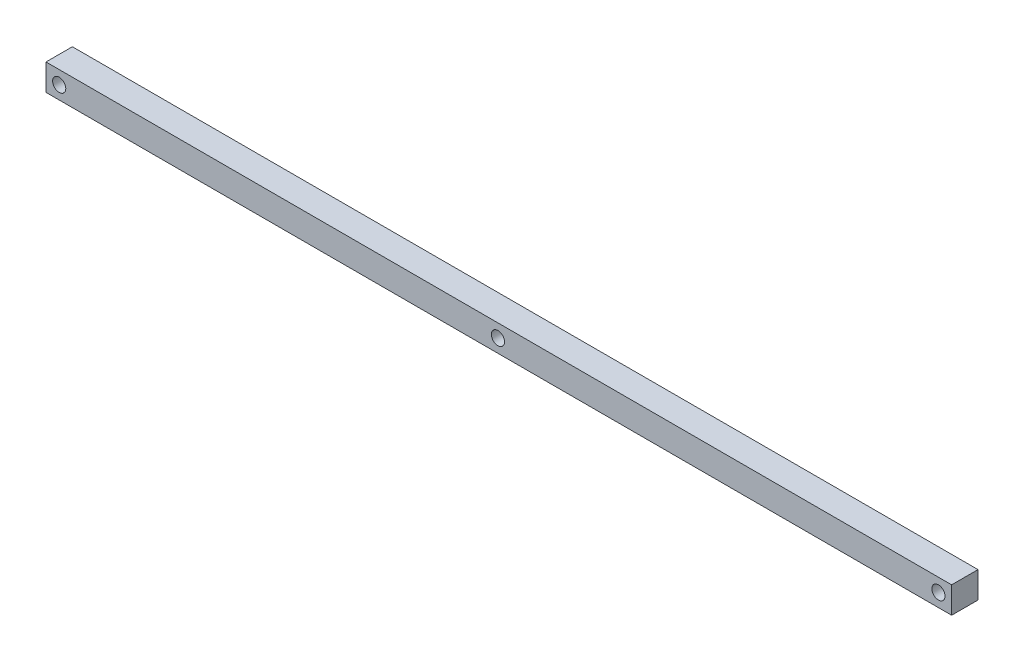
SolidWorks part; units mm, degrees
ref_plane "Front Plane" through (0, 0, 0) normal (0, 0, 1) x (1, 0, 0)
ref_plane "Top Plane" through (0, 0, 0) normal (0, 1, 0) x (1, 0, 0)
ref_plane "Right Plane" through (0, 0, 0) normal (1, 0, 0) x (0, 0, -1)
sketch "Sketch1" plane through (0, 0, 0) normal (0, 0, 1) x (1, 0, 0)
  line L0 (500, 0) -> (-500, 0) construction
  line L1 (515, 15) -> (-515, 15)
  line L2 (515, 15) -> (515, -15)
  line L3 (515, -15) -> (-515, -15)
  line L4 (-515, 15) -> (-515, -15)
  line L5 (515, 15) -> (-515, -15) construction
  line L6 (515, -15) -> (-515, 15) construction
  circle A0 centre (-500, 0) radius 7.5
  circle A1 centre (500, 0) radius 7.5
  circle A2 centre (-1, 0) radius 7.5
  point P0 (0, 0)
  point P8 (0, 0)
  dimension "D2" = 15
  dimension "D1" = 30
  dimension "D3" = 1000
  dimension "D4" = 15
  dimension "D5" = 499
extrude "Boss-Extrude1" add sketch "Sketch1" along normal mid plane 30
equation "\"A\"= 200"
equation "\"hole_diameter\"=15"
equation "\"D2@Sketch1\"=\"hole_diameter\""
equation "\"D3@Sketch1\"=5*\"A\""
equation "\"D4@Sketch1\"=\"hole_diameter\""
equation "\"r15\"=499"
equation "\"D5@Sketch1\"=\"r15\""
